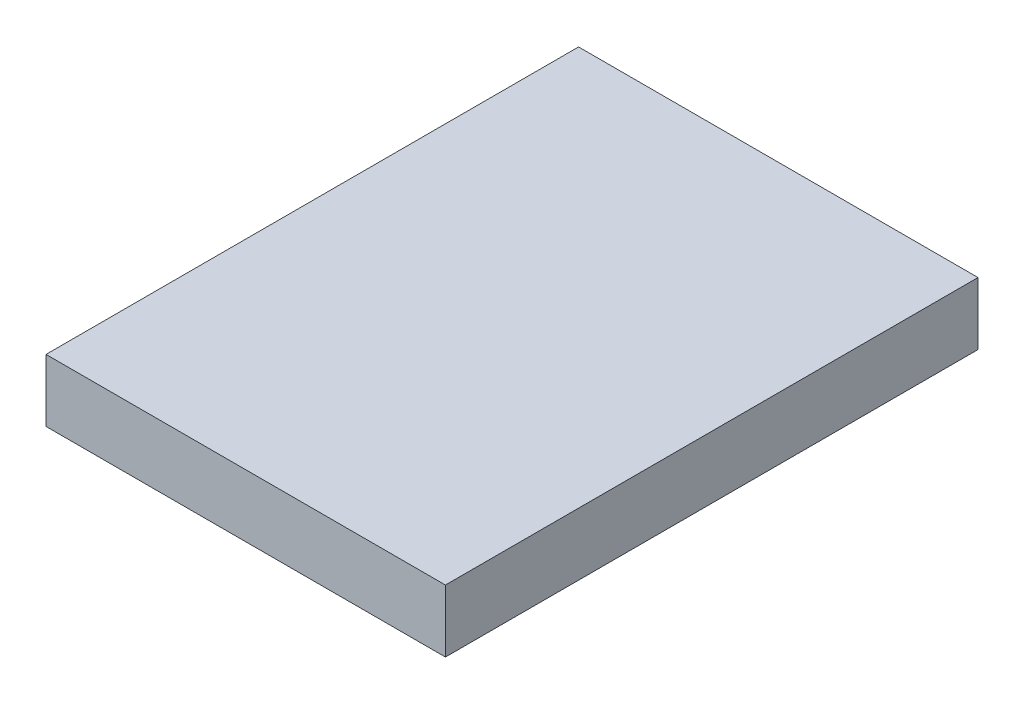
SolidWorks part; units mm, degrees
ref_plane "Front Plane" through (0, 0, 0) normal (0, 0, 1) x (1, 0, 0)
ref_plane "Top Plane" through (0, 0, 0) normal (0, 1, 0) x (1, 0, 0)
ref_plane "Right Plane" through (0, 0, 0) normal (1, 0, 0) x (0, 0, -1)
sketch "Sketch1" plane through (0, 0, 0) normal (0, 1, 0) x (1, 0, 0)
  line L1 (-24, -32) -> (24, -32)
  line L2 (-24, -32) -> (-24, 32)
  line L3 (-24, 32) -> (24, 32)
  line L4 (24, -32) -> (24, 32)
  line L5 (-24, -32) -> (24, 32) construction
  line L6 (-24, 32) -> (24, -32) construction
  point P0 (0, 0)
  dimension "D1" = 64
  dimension "D2" = 48
extrude "Boss-Extrude1" add sketch "Sketch1" along normal blind 7.5
